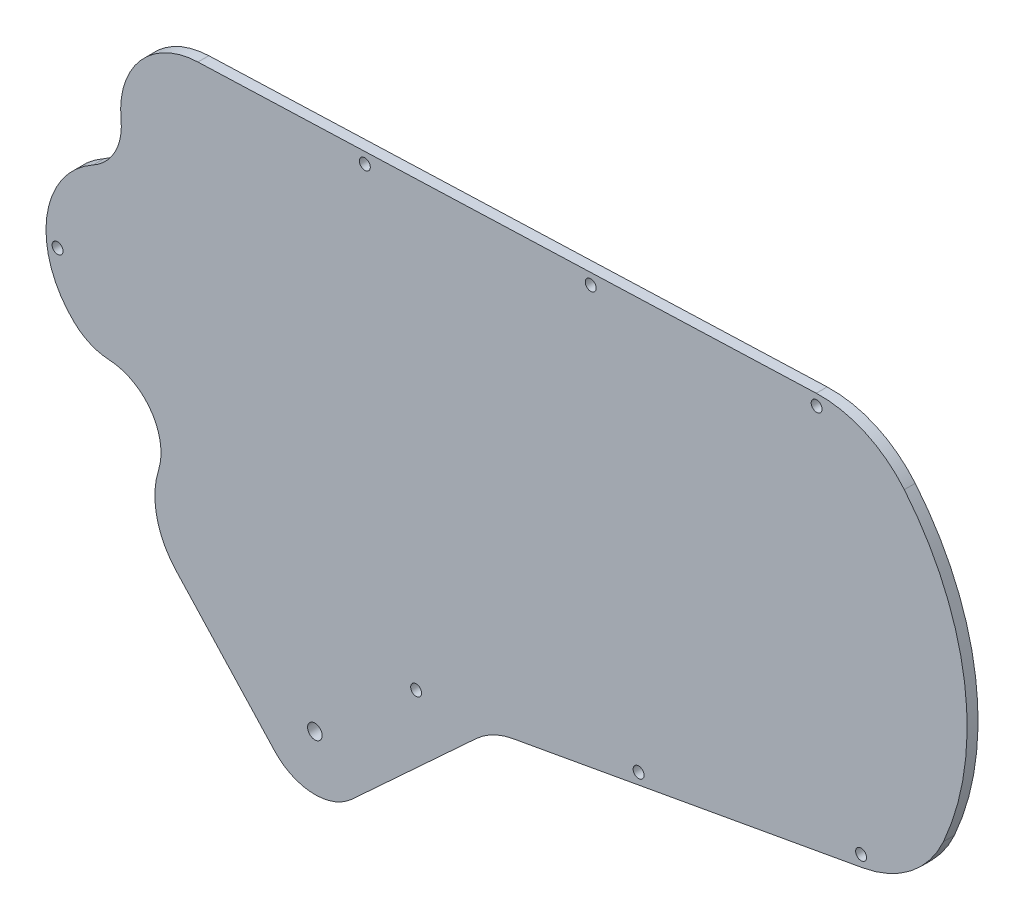
SolidWorks part; units mm, degrees
material "1060 Alloy"
ref_plane "Front Plane" through (0, 0, 0) normal (0, 0, 1) x (1, 0, 0)
ref_plane "Top Plane" through (0, 0, 0) normal (0, 1, 0) x (1, 0, 0)
ref_plane "Right Plane" through (0, 0, 0) normal (1, 0, 0) x (0, 0, -1)
sketch "Sketch1" plane through (0, 0, 0) normal (0, 0, 1) x (1, 0, 0)
  line L0 (86.8854, -33.5) -> (-137.2004, -33.5) construction
  line L1 (-111.886, 49.4802) -> (83.0489, 41.2139) construction
  line L2 (-115.2069, 49.6211) -> (-101.035, -81.6153) construction
  line L3 (-97.8208, -80.7688) -> (92.1699, -30.731) construction
  line L4 (78.7977, 41.3942) -> (86.7407, -32.1609) construction
  line L5 (-108.121, -15.9971) -> (82.7692, 4.6166) construction
  line L6 (91, -33.5) -> (-88.5, -33.5) construction
  line L7 (-97.4673, 5.5) -> (-155.3054, 5.5) construction
  line L8 (-138.3, -14) -> (-155.3054, -14) construction
  line L9 (-138.3, 5.5) -> (-138.3, -33.5) construction
  line L10 (-155.3054, 5.5) -> (-155.3054, -33.5) construction
  line L11 (40.0178, 33.5) -> (40.0178, -33.5) construction
  line L12 (-101.0559, -81.4218) -> (-90.5433, -79.5278)
  line L13 (-91.5, 33.5) -> (88, 33.5) construction
  line L14 (-68.3, -21.5) -> (-107.0746, -25.6872) construction
  line L15 (-138.3, -5.25) -> (-81.5148, -93.5701) construction
  line L17 (-119.5948, -74.4106) -> (-92.5405, -103.7404)
  line L18 (-71.3446, -104.5958) -> (-37.2211, -73.1197)
  line L19 (-27.1401, -68.1042) -> (68.9251, -50.7959)
  line L20 (-117.3596, 49.3503) -> (56.0883, 55.6165)
  circle A0 centre (40.0178, 0) radius 4.25
  circle A1 centre (-112.8181, 27.5) radius 13 construction
  circle A2 centre (-103.4238, -59.4942) radius 13 construction
  arc A3 (-91.5, 33.5) -> (-88.5, -33.5) centre (-18.0922, 3.2198) ccw construction
  circle A4 centre (-68.3, -21.5) radius 2.25
  circle A6 centre (-138.3, -5.25) radius 2
  circle A7 centre (-138.3, -22.75) radius 2
  arc A8 (-142.3827, 10.6321) -> (-147.5429, -29.3643) centre (-130.3054, -11.2571) ccw
  arc A9 (-147.5429, -29.3643) -> (-137.2004, -33.5) centre (-137.2004, -18.5) ccw
  circle A10 centre (-112.8181, 27.5) radius 22
  arc A11 (68.9251, -50.7959) -> (91, -33.5) centre (63.6055, -21.2712) ccw
  circle A12 centre (-103.4238, -59.4942) radius 22
  arc A13 (91, -33.5) -> (80.2612, 44.7896) centre (22.6589, -2.9929) ccw
  arc A14 (91, -33.5) -> (88, 33.5) centre (22.6589, -2.9929) ccw construction
  arc A17 (-124.4228, -52.9336) -> (-137.9704, -33.4802) centre (-138.7403, -48.4604) ccw
  arc A18 (-142.3827, 10.6321) -> (-134.7058, 25.2795) centre (-149.6292, 23.7656) ccw
  circle A19 centre (-74.1, 1.7) radius 2.25
  circle A20 centre (-65.4, 20.2) radius 2.25
  circle A21 centre (8.1, 8.2) radius 2.25
  circle A23 centre (18.5, -8.7) radius 2.25
  circle A25 centre (78, -0.1) radius 2.25
  circle A26 centre (75.9, -21.8) radius 2.25
  circle A27 centre (73, 22.4) radius 2.25
  arc A28 (80.2612, 44.7896) -> (56.0883, 55.6165) centre (57.1714, 25.636) ccw
  circle A30 centre (-81.5148, -93.5701) radius 2
  circle A36 centre (-114.2138, 40.4249) radius 1.75
  circle A37 centre (-99.8933, 28.8957) radius 1.75
  circle A38 centre (-111.4224, 14.5751) radius 1.75
  circle A39 centre (-125.743, 26.1043) radius 1.75
  circle A40 centre (-104.8196, -46.5694) radius 1.75
  circle A41 centre (-90.499, -58.0985) radius 1.75
  circle A42 centre (-102.0281, -72.4191) radius 1.75
  circle A43 centre (-116.3487, -60.89) radius 1.75
  circle A44 centre (40.0178, 0) radius 35 construction
  circle A45 centre (40.0178, 0) radius 43
  circle A49 centre (-103.4238, -59.4942) radius 16
  circle A50 centre (-112.8181, 27.5) radius 16
  circle A51 centre (-112.8181, 27.5) radius 9.75
  circle A52 centre (-103.4238, -59.4942) radius 9.75
  arc A53 (91, -33.5) -> (88, 33.5) centre (22.6589, -2.9929) ccw construction
  arc A54 (-92.5405, -103.7404) -> (-71.3446, -104.5958) centre (-81.5148, -93.5701) ccw
  arc A55 (-27.1401, -68.1042) -> (-37.2211, -73.1197) centre (-23.5699, -87.9191) ccw
  circle A56 centre (-68.3, -21.5) radius 2.25 construction
  circle A57 centre (-74.1, 1.7) radius 2.25 construction
  circle A58 centre (-65.4, 20.2) radius 2.25 construction
  circle A59 centre (18.5, -8.7) radius 2.25 construction
  circle A60 centre (8.1, 8.2) radius 2.25 construction
  circle A61 centre (75.9, -21.8) radius 2.25 construction
  circle A62 centre (78, -0.1) radius 2.25 construction
  circle A63 centre (73, 22.4) radius 2.25 construction
  point P52 (82.7692, 4.6166)
  point P109 (-112.8181, 27.5)
  point P118 (-103.4238, -59.4942)
  point P135 (0, 0)
  dimension "D5" = 4
  dimension "D6" = 25
  dimension "D9" = 15
  dimension "D13" = 30
  dimension "D14" = 26
  dimension "D11" = 44
  dimension "D15" = 3.5
  dimension "D12" = 70
  dimension "D19" = 8.5
  dimension "D20" = 19.5
  dimension "D22" = 32
  dimension "D24" = 4
  dimension "D26" = 55
  dimension "D2" = 39
  dimension "D3" = 70
  dimension "D4" = 17.5
  dimension "D7" = 14
  dimension "D8" = 10
  dimension "D10" = 87.5
  dimension "D21" = 192
  dimension "D23" = 39
  dimension "D25" = 105
  dimension "D18" = 8
  dimension "D16" = 4
  dimension "D17" = 4
extrude "Boss-Extrude1" add sketch "Sketch1" along normal blind 3
sketch "Sketch2" plane through (0, 0, 3) normal (0, 0, 1) x (1, 0, 0)
  line L0 (68.3931, -47.8434) -> (7.3358, -58.8443) construction
  line L2 (7.3358, -58.8443) -> (-53.7216, -69.8452) construction
  line L7 (56.1966, 52.6184) -> (-113.5041, 46.4876)
  line L8 (56.1966, 52.6184) -> (-113.5041, 46.4876)
  line L9 (-67.8034, 48.1386) -> (-5.8034, 50.3785) construction
  line L10 (-5.8034, 50.3785) -> (56.1966, 52.6184) construction
  line L13 (-117.3897, -72.3766) -> (-90.3354, -101.7064)
  line L14 (-73.3786, -102.3907) -> (-39.2552, -70.9146)
  line L15 (-27.672, -65.1517) -> (68.3931, -47.8434)
  line L17 (-117.3897, -72.3766) -> (-90.3354, -101.7064) construction
  line L18 (-73.3786, -102.3907) -> (-39.2552, -70.9146) construction
  line L19 (-110.3186, -80.0424) -> (68.3931, -47.8434) construction
  circle A0 centre (7.3358, -58.8443) radius 1.5
  circle A2 centre (-53.7216, -69.8452) radius 1.5
  arc A14 (77.9522, 42.8742) -> (56.1966, 52.6184) centre (57.1714, 25.636) ccw
  arc A15 (77.9522, 42.8742) -> (56.1966, 52.6184) centre (57.1714, 25.636) ccw
  arc A16 (68.3931, -47.8434) -> (88.2606, -32.2771) centre (63.6055, -21.2712) ccw
  arc A17 (-114.7845, -75.2008) -> (-103.8362, -78.8745) centre (-105.964, -67.0646) ccw construction
  circle A21 centre (68.3931, -47.8434) radius 1.5
  circle A23 centre (56.1966, 52.6184) radius 1.5
  circle A24 centre (-5.8034, 50.3785) radius 1.5
  circle A27 centre (-67.8034, 48.1386) radius 1.5
  arc A28 (-113.5041, 46.4876) -> (-131.7211, 25.5823) centre (-112.8181, 27.5) ccw
  arc A29 (-140.9335, 8.0053) -> (-131.7211, 25.5823) centre (-149.6292, 23.7656) ccw
  arc A30 (-140.9335, 8.0053) -> (-145.4744, -27.1914) centre (-130.3054, -11.2571) ccw
  arc A31 (-145.4744, -27.1914) -> (-137.8164, -30.4842) centre (-137.2004, -18.5) ccw
  arc A32 (-121.5593, -53.8282) -> (-137.8164, -30.4842) centre (-138.7403, -48.4604) ccw
  arc A33 (-121.5593, -53.8282) -> (-117.3897, -72.3766) centre (-103.4238, -59.4942) ccw
  arc A34 (-90.3354, -101.7064) -> (-73.3786, -102.3907) centre (-81.5148, -93.5701) ccw
  arc A35 (-27.672, -65.1517) -> (-39.2552, -70.9146) centre (-23.5699, -87.9191) ccw
  arc A36 (88.2606, -32.2771) -> (77.9522, 42.8742) centre (22.6589, -2.9929) ccw
  arc A37 (-113.5041, 46.4876) -> (-131.7211, 25.5823) centre (-112.8181, 27.5) ccw construction
  arc A38 (-140.9335, 8.0053) -> (-131.7211, 25.5823) centre (-149.6292, 23.7656) ccw construction
  arc A39 (-140.9335, 8.0053) -> (-145.4744, -27.1914) centre (-130.3054, -11.2571) ccw construction
  arc A40 (-145.4744, -27.1914) -> (-137.8164, -30.4842) centre (-137.2004, -18.5) ccw construction
  arc A41 (-121.5593, -53.8282) -> (-137.8164, -30.4842) centre (-138.7403, -48.4604) ccw construction
  arc A42 (-121.5593, -53.8282) -> (-117.3897, -72.3766) centre (-103.4238, -59.4942) ccw construction
  arc A43 (-90.3354, -101.7064) -> (-73.3786, -102.3907) centre (-81.5148, -93.5701) ccw construction
  arc A44 (-27.672, -65.1517) -> (-39.2552, -70.9146) centre (-23.5699, -87.9191) ccw construction
  arc A45 (88.2606, -32.2771) -> (77.9522, 42.8742) centre (22.6589, -2.9929) ccw construction
  circle A47 centre (-152.1337, -14) radius 1.5
  arc A51 (68.3931, -47.8434) -> (88.2606, -32.2771) centre (63.6055, -21.2712) ccw
  point P2 (-152.1337, -14)
  point P3 (-137.8164, -22.75)
  dimension "D4" = 3
  dimension "D2" = 62
  dimension "D3" = 14.3174
  dimension "D1" = 3
extrude "Cut-Extrude1" cut sketch "Sketch2" against normal through all
